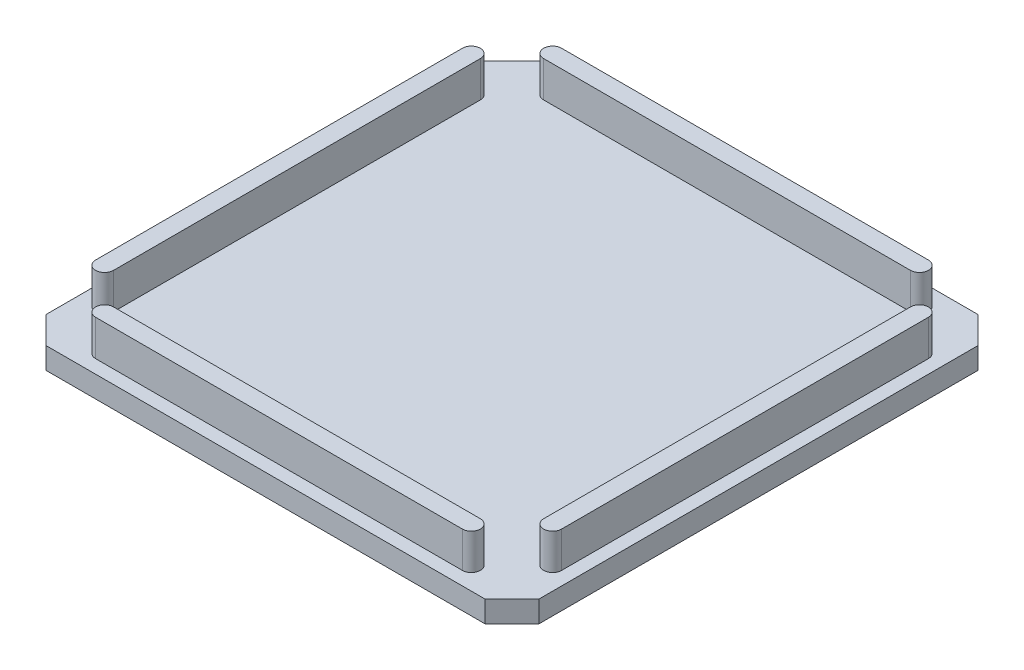
SolidWorks part; units mm, degrees
ref_plane "Front Plane" through (0, 0, 0) normal (0, 0, 1) x (1, 0, 0)
ref_plane "Top Plane" through (0, 0, 0) normal (0, 1, 0) x (1, 0, 0)
ref_plane "Right Plane" through (0, 0, 0) normal (1, 0, 0) x (0, 0, -1)
sketch "Sketch1" plane through (0, 0, 0) normal (0, 1, 0) x (1, 0, 0)
  line L0 (-27.5, 24.5) -> (-24.5, 27.5)
  line L1 (-24.5, -27.5) -> (24.5, -27.5)
  line L2 (-27.5, -24.5) -> (-27.5, 24.5)
  line L3 (-24.5, 27.5) -> (24.5, 27.5)
  line L4 (27.5, -24.5) -> (27.5, 24.5)
  line L5 (-27.5, -27.5) -> (27.5, 27.5) construction
  line L6 (-27.5, 27.5) -> (27.5, -27.5) construction
  line L7 (-27.5, -24.5) -> (-24.5, -27.5)
  line L8 (24.5, -27.5) -> (27.5, -24.5)
  line L9 (24.5, 27.5) -> (27.5, 24.5)
  point P0 (0, 0)
  point P10 (0, 0)
  dimension "D1" = 55
extrude "Boss-Extrude1" add sketch "Sketch1" along normal blind 2.4
sketch "Sketch2" plane through (0, 2.4, 0) normal (0, 1, 0) x (1, 0, 0)
  line L0 (-25, -20.4656) -> (-25, 20.4656) construction
  line L1 (-24, -20.4656) -> (-24, 20.4656)
  line L2 (-26, -20.4656) -> (-26, 20.4656)
  line L3 (-25, 0) -> (0, 0) construction
  line L4 (-27.5, 24.5) -> (-27.5, -24.5) construction
  line L5 (-20.4656, 24) -> (20.4656, 24)
  line L6 (-20.4656, 26) -> (20.4656, 26)
  line L7 (24, 20.4656) -> (24, -20.4656)
  line L8 (26, 20.4656) -> (26, -20.4656)
  line L9 (20.4656, -24) -> (-20.4656, -24)
  line L10 (20.4656, -26) -> (-20.4656, -26)
  arc A0 (-24, -20.4656) -> (-26, -20.4656) centre (-25, -20.4656) cw
  arc A1 (-24, 20.4656) -> (-26, 20.4656) centre (-25, 20.4656) ccw
  circle A2 centre (0, 0) radius 5.2235 construction
  arc A3 (20.4656, 24) -> (20.4656, 26) centre (20.4656, 25) ccw
  arc A4 (-20.4656, 24) -> (-20.4656, 26) centre (-20.4656, 25) cw
  arc A5 (24, -20.4656) -> (26, -20.4656) centre (25, -20.4656) ccw
  arc A6 (24, 20.4656) -> (26, 20.4656) centre (25, 20.4656) cw
  arc A7 (-20.4656, -24) -> (-20.4656, -26) centre (-20.4656, -25) ccw
  arc A8 (20.4656, -24) -> (20.4656, -26) centre (20.4656, -25) cw
  point P3 (-25, 0)
  point P34 (0, 0)
  dimension "D3" = 2.5
  dimension "D1" = 1
  dimension "D2" = 1
  dimension "D4" = 4
extrude "Boss-Extrude2" add sketch "Sketch2" along normal blind 4
